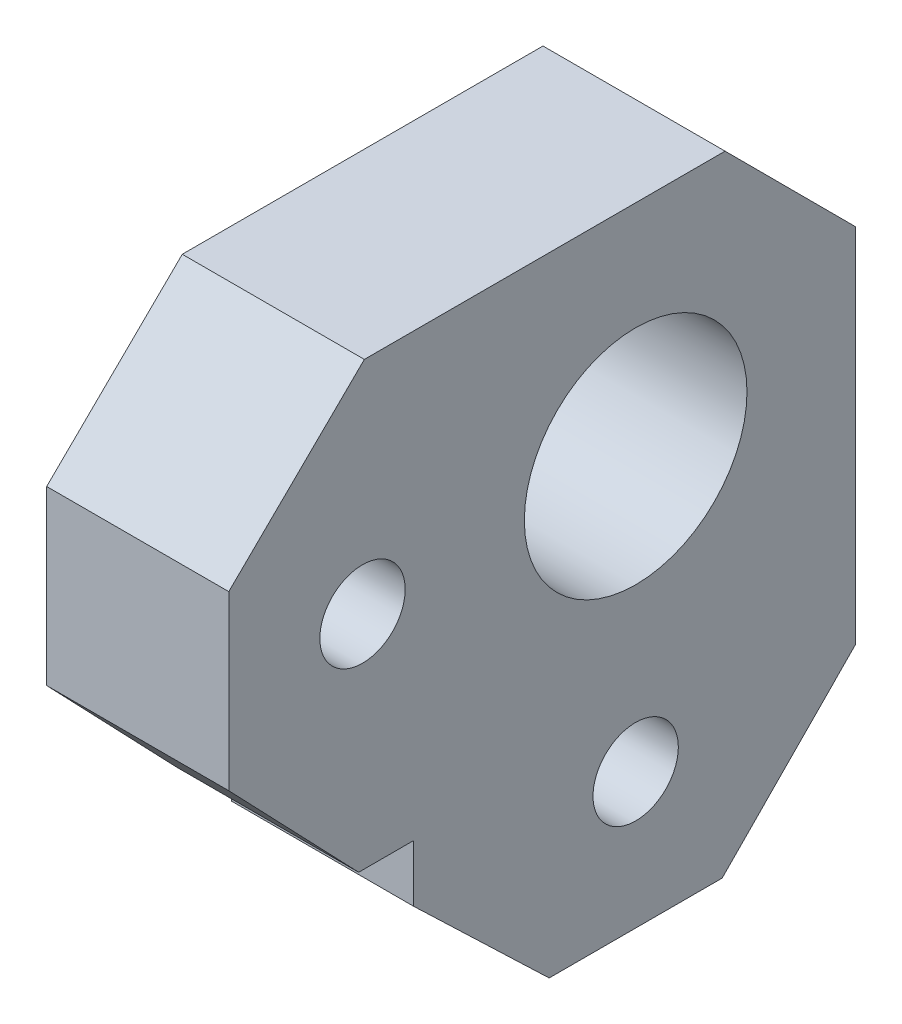
SolidWorks part; units mm, degrees
ref_plane "Front Plane" through (0, 0, 0) normal (0, 0, 1) x (1, 0, 0)
ref_plane "Top Plane" through (0, 0, 0) normal (0, 1, 0) x (1, 0, 0)
ref_plane "Right Plane" through (0, 0, 0) normal (1, 0, 0) x (0, 0, -1)
sketch "Sketch1" plane through (0, 0, 0) normal (1, 0, 0) x (0, 0, -1)
  line L0 (9.2553, -5.8315) -> (4.5745, -10.5923)
  line L1 (-7.9995, 11.4835) -> (4.6781, 11.4835)
  line L2 (-12.7647, 6.7983) -> (-12.7647, 0.7388)
  line L3 (-1.5038, -10.5923) -> (-6.2647, -6.0315)
  line L4 (-8.1995, -4.0264) -> (-12.7647, 0.7388)
  line L5 (4.6781, 11.4835) -> (9.2553, 6.8986)
  line L6 (-7.9995, 11.4835) -> (-12.7647, 6.7983)
  line L7 (1.5353, 3.7685) -> (1.5353, -5.8315) construction
  line L8 (9.2553, 6.8986) -> (9.2553, -5.8315)
  line L9 (1.5353, 3.7685) -> (-8.0647, 3.7685) construction
  line L10 (-1.5038, -10.5923) -> (4.5745, -10.5923)
  line L12 (-6.2647, -6.0315) -> (-6.2647, -4.0264)
  line L13 (-6.2647, -4.0264) -> (-8.1995, -4.0264)
  circle A0 centre (1.5353, 3.7685) radius 3.9125
  circle A1 centre (-8.0647, 3.7685) radius 1.5
  circle A3 centre (1.5353, -5.8315) radius 1.5
  point P15 (-12.5647, 3.7685)
  point P22 (1.5353, -10.5923)
extrude "Boss-Extrude1" add sketch "Sketch1" along normal blind 6.4
sketch "Sketch2" plane through (0, 0, 0) normal (-1, 0, 0) x (0, 0, 1)
  line L0 (4.7647, -1.5264) -> (4.7647, -2.5264)
  line L1 (4.7647, -2.5264) -> (3.7647, -2.5264)
  line L3 (4.7647, -1.5264) -> (3.7647, -1.5264)
  line L4 (3.7647, -2.5264) -> (3.7647, -1.5264)
  dimension "D1" = 1
  dimension "D2" = 1
extrude "Cut-Extrude1" cut sketch "Sketch2" against normal blind 0.01
